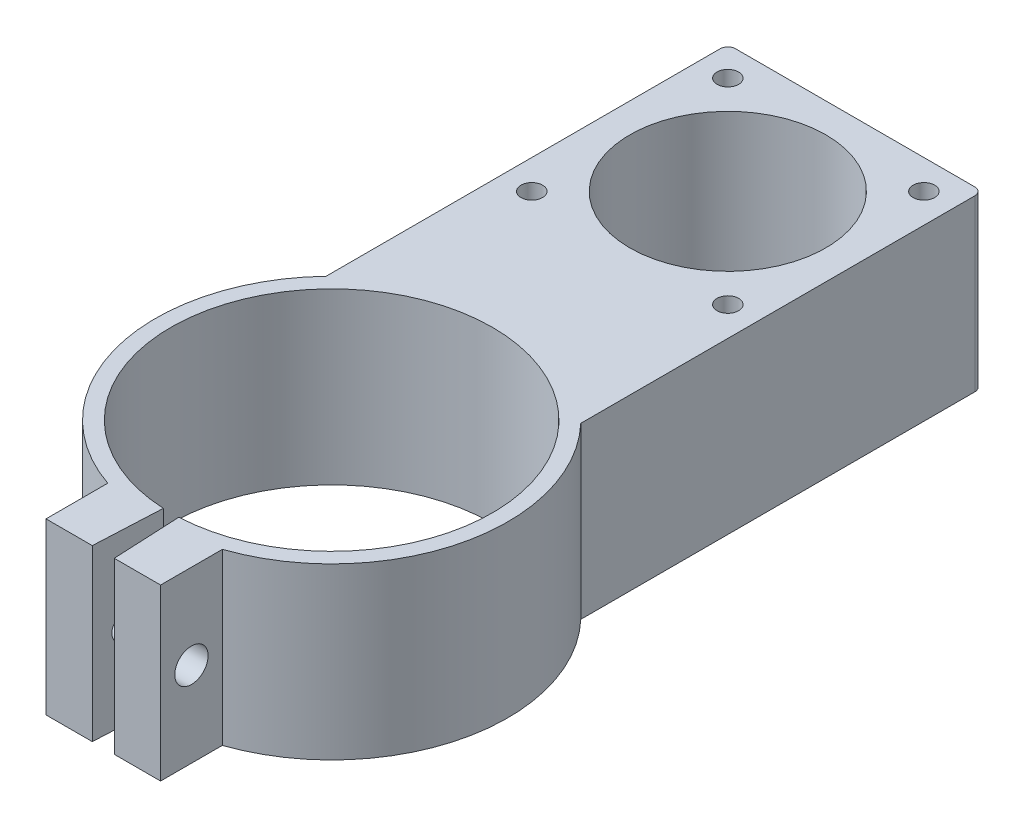
SolidWorks part; units mm, degrees
ref_plane "Front Plane" through (0, 0, 0) normal (0, 0, 1) x (1, 0, 0)
ref_plane "Top Plane" through (0, 0, 0) normal (0, 1, 0) x (1, 0, 0)
ref_plane "Right Plane" through (0, 0, 0) normal (1, 0, 0) x (0, 0, -1)
sketch "Sketch1" plane through (0, 0, 0) normal (0, 1, 0) x (1, 0, 0)
  line L0 (0, 34.5201) -> (0, -34.5201) construction
  line L1 (0, 0) -> (1.1366, -23.6451) construction
  line L2 (0, 0) -> (-1.1366, -23.6451) construction
  line L3 (1, -20.804) -> (1.4222, -29.5877)
  line L4 (1.4222, -29.5877) -> (7.4222, -29.5877)
  line L5 (7.4222, -29.5877) -> (7.4222, -21.5877)
  line L6 (-7.4222, -29.5877) -> (-7.4222, -21.5877)
  line L7 (-1.4222, -29.5877) -> (-7.4222, -29.5877)
  line L8 (-1, -20.804) -> (-1.4222, -29.5877)
  line L9 (-16.5, 67.828) -> (16.5, 67.828)
  line L10 (16.5, 67.828) -> (16.5, 15.7755)
  line L11 (-16.5, 67.828) -> (-16.5, 15.7755)
  circle A0 centre (0, 0) radius 20.828 construction
  arc A1 (1, -20.804) -> (-1, -20.804) centre (0, 0) ccw
  arc A2 (7.4222, -21.5877) -> (16.5, 15.7755) centre (0, 0) ccw
  arc A3 (1.096, -22.8017) -> (-1.096, -22.8017) centre (0, 0) ccw construction
  arc A4 (-16.5, 15.7755) -> (-7.4222, -21.5877) centre (0, 0) ccw
  point P5 (0, 0)
  point P8 (1, -20.804)
  point P9 (1, -20.804)
  point P10 (-1, -20.804)
  point P11 (0, -20.828)
  point P25 (0, 22.828)
  point P29 (0, 67.828)
  dimension "D1" = 41.656
  dimension "D7" = 45
  dimension "D2" = 1
  dimension "D4" = 6
  dimension "D5" = 8
  dimension "D6" = 16.5
  dimension "D3" = 2
extrude "Boss-Extrude1" add sketch "Sketch1" along normal blind 22
sketch "Sketch4" plane through (-7.4222, 0, 0) normal (-1, 0, 0) x (0, 0, 1)
  line L0 (21.5877, 22) -> (29.5877, 0) construction
  circle A0 centre (25.5877, 11) radius 1.5875
  dimension "D1" = 3.175
extrude "Cut-Extrude1" cut sketch "Sketch4" against normal up to next
sketch "Sketch5" plane through (7.4222, 0, 0) normal (1, 0, 0) x (0, 0, -1)
  circle A0 centre (-25.5877, 11) radius 2.159
  dimension "D1" = 4.318
extrude "Cut-Extrude2" cut sketch "Sketch5" against normal up to next
sketch "Sketch7" plane through (0, 0, 0) normal (0, -1, 0) x (1, 0, 0)
  line L0 (16.5, -67.828) -> (-16.5, -67.828) construction
  circle A0 centre (0, -51.328) radius 12.7
  dimension "D1" = 25.4
  dimension "D2" = 16.5
extrude "Cut-Extrude3" cut sketch "Sketch7" against normal through all
sketch "Sketch8" plane through (0, 22, 0) normal (0, 1, 0) x (1, 0, 0)
  circle A0 centre (12.7, 64.028) radius 1.397
  circle A1 centre (0, 51.328) radius 12.7 construction
  circle A2 centre (12.7, 38.628) radius 1.397
  circle A3 centre (-12.7, 38.628) radius 1.397
  circle A4 centre (-12.7, 64.028) radius 1.397
  point P13 (0, 51.328)
  dimension "D1" = 2.794
  dimension "D2" = 12.7
  dimension "D3" = 12.7
  dimension "D4" = 4
extrude "Cut-Extrude4" cut sketch "Sketch8" against normal through all
sketch "Sketch9" plane through (0, 0, 0) normal (0, -1, 0) x (1, 0, 0)
  line L0 (-13.5, -34.628) -> (13.5, -34.628)
  line L1 (-13.5, -34.628) -> (-13.5, -19.6348)
  line L2 (13.5, -34.628) -> (13.5, -19.6348)
  line L3 (-16.5, -67.828) -> (-16.5, -15.7755) construction
  line L4 (16.5, -15.7755) -> (16.5, -67.828) construction
  circle A0 centre (0, -51.328) radius 12.7 construction
  arc A3 (-1.144, 23.8005) -> (1.144, 23.8005) centre (0, 0) ccw
  arc A4 (-13.5, -19.6348) -> (13.5, -19.6348) centre (0, 0) ccw
  dimension "D1" = 16.7
  dimension "D3" = 3
  dimension "D4" = 3
  dimension "D2" = 3
extrude "Cut-Extrude5" cut sketch "Sketch9" against normal offset from surface (19 mm away) 3 up to face at (-12.7, 22, -62.631)
fillet "Fillet1" radius 1 2 edges at (16.5, 11, -67.828) (-16.5, 11, -67.828)
